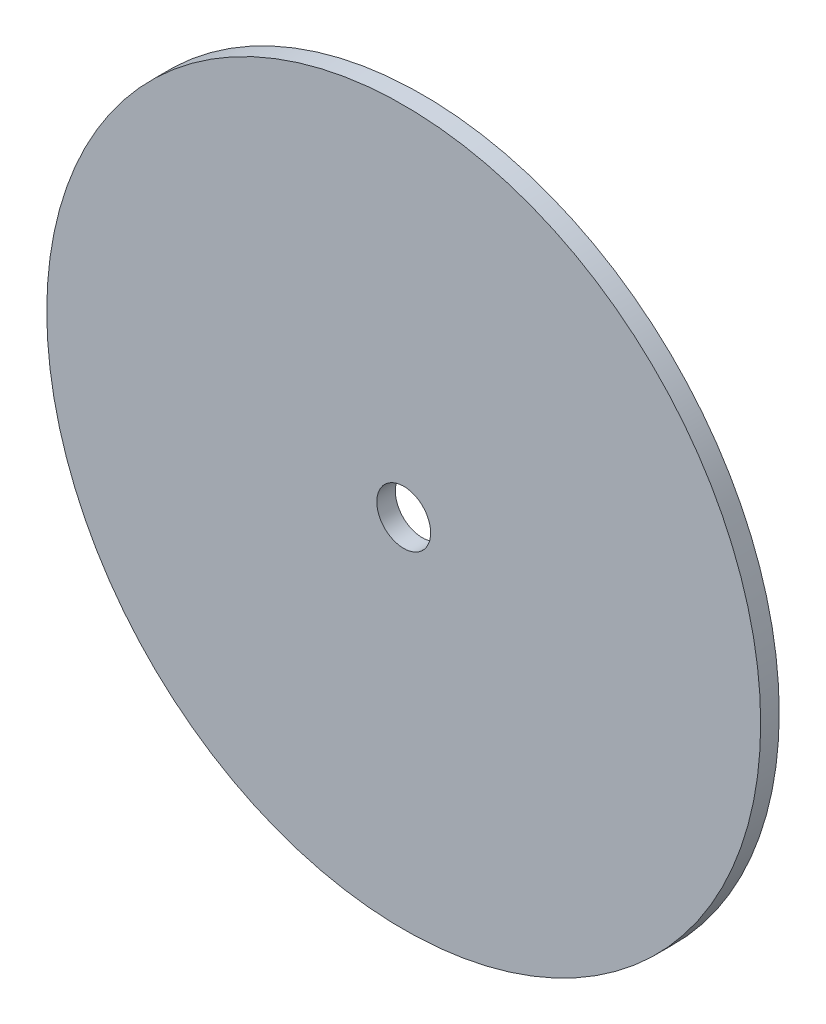
SolidWorks part; units mm, degrees
ref_plane "Front Plane" through (0, 0, 0) normal (0, 0, 1) x (1, 0, 0)
ref_plane "Top Plane" through (0, 0, 0) normal (0, 1, 0) x (1, 0, 0)
ref_plane "Right Plane" through (0, 0, 0) normal (1, 0, 0) x (0, 0, -1)
sketch "Sketch1" plane through (0, 0, 0) normal (0, 0, 1) x (1, 0, 0)
  circle A0 centre (0, 0) radius 59.655
  dimension "D1" = 119.31
extrude "Boss-Extrude1" add sketch "Sketch1" along normal mid plane 3.1
sketch "Sketch2" plane through (0, 0, 1.55) normal (0, 0, 1) x (1, 0, 0)
  circle A0 centre (0, 0) radius 4.5
  dimension "D1" = 9
extrude "Cut-Extrude1" cut sketch "Sketch2" against normal through all
